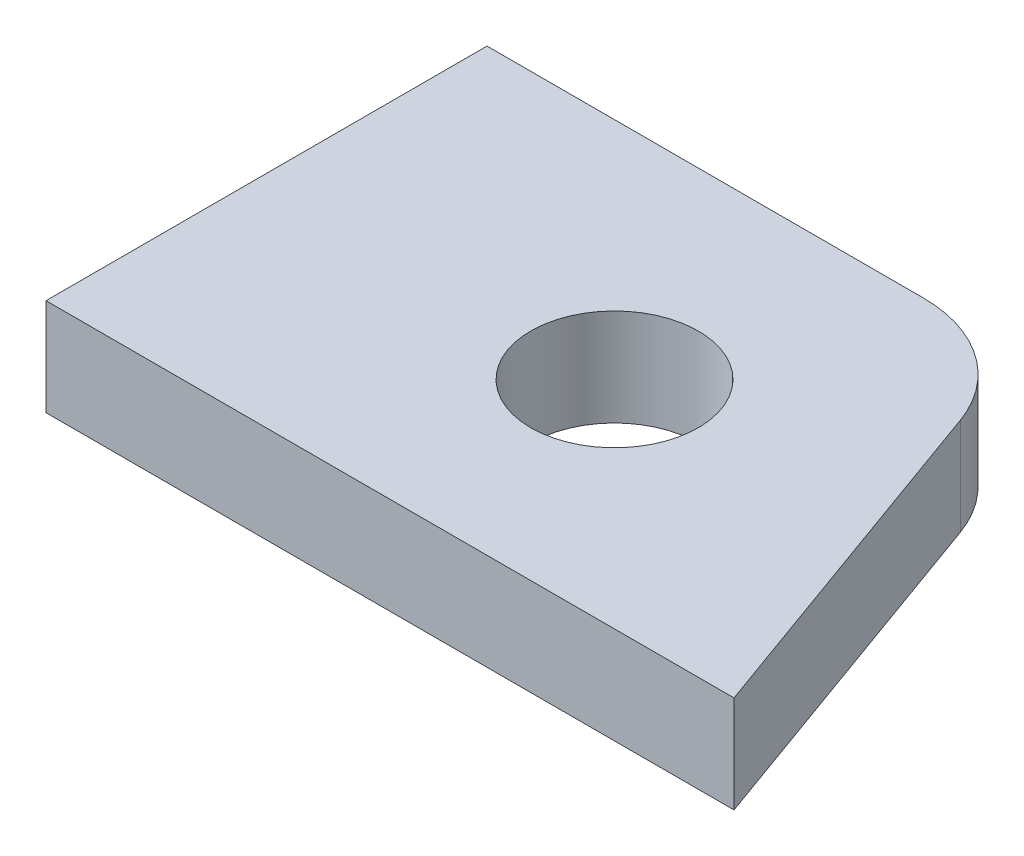
SolidWorks part; units mm, degrees
ref_plane "Front Plane" through (0, 0, 0) normal (0, 0, 1) x (1, 0, 0)
ref_plane "Top Plane" through (0, 0, 0) normal (0, 1, 0) x (1, 0, 0)
ref_plane "Right Plane" through (0, 0, 0) normal (1, 0, 0) x (0, 0, -1)
sketch "Sketch1" plane through (0, 0, 0) normal (0, 1, 0) x (1, 0, 0)
  line L0 (0, 0) -> (78, 0)
  line L1 (0, 0) -> (0, 50)
  line L2 (0, 50) -> (49.4576, 50)
  line L3 (63.5709, 40.0808) -> (78, 0)
  circle A0 centre (39.9523, 24.5) radius 9.5
  arc A1 (49.4576, 50) -> (63.5709, 40.0808) centre (49.4576, 35) cw
  point P9 (60, 50)
  dimension "D4" = 19
  dimension "D7" = 15
  dimension "D1" = 27.5
  dimension "D2" = 50
  dimension "D3" = 60
  dimension "D5" = 25.5
  dimension "D6" = 78
extrude "Boss-Extrude1" add sketch "Sketch1" along normal blind 11
